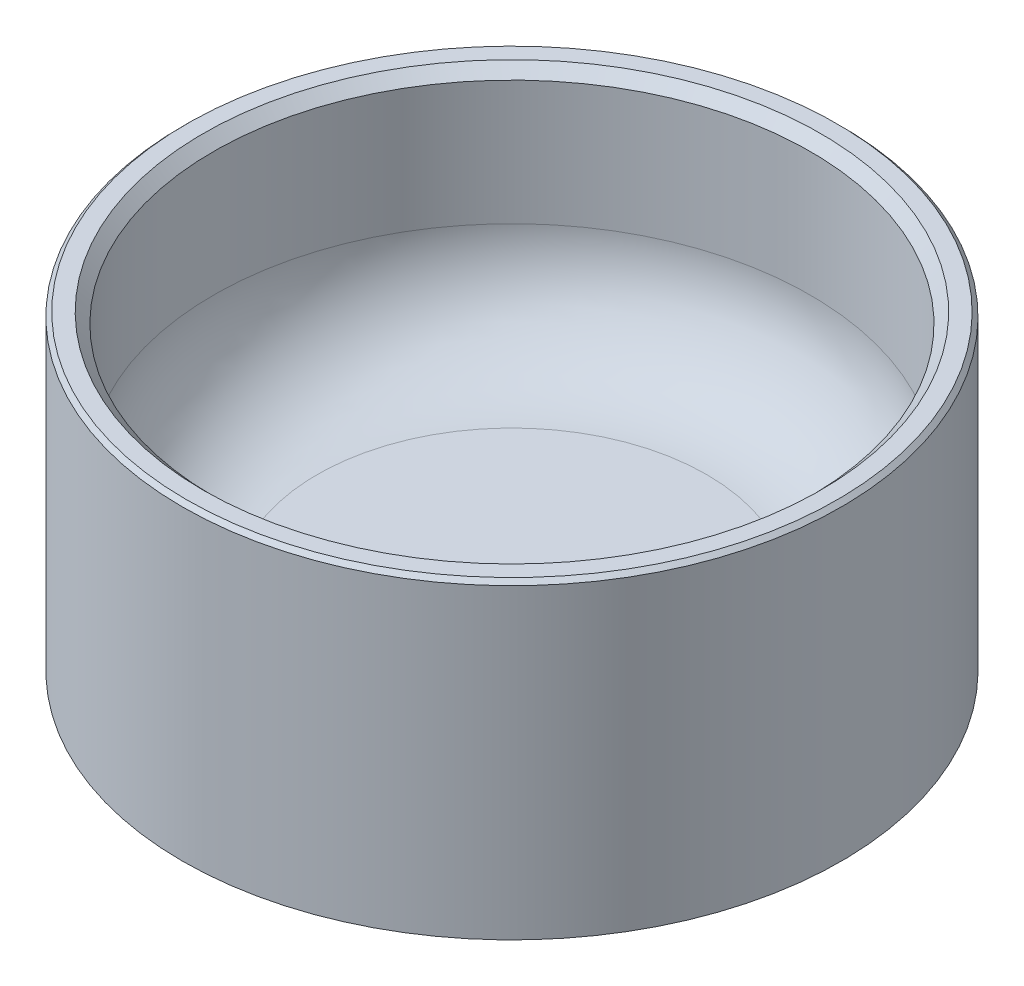
SolidWorks part; units mm, degrees
ref_plane "Front Plane" through (0, 0, 0) normal (0, 0, 1) x (1, 0, 0)
ref_plane "Top Plane" through (0, 0, 0) normal (0, 1, 0) x (1, 0, 0)
ref_plane "Right Plane" through (0, 0, 0) normal (1, 0, 0) x (0, 0, -1)
sketch "Sketch1" plane through (0, 0, 0) normal (0, 0, 1) x (1, 0, 0)
  line L0 (0, 0) -> (-12.4, 0)
  line L1 (-15.9, -2) -> (-15.9, 13)
  line L2 (-15.9, 13) -> (-14.4, 13)
  line L3 (-14.4, 13) -> (-14.4, 6.5)
  line L4 (-9.4, 1.5) -> (0, 1.5)
  line L5 (0, 1.5) -> (0, 0) construction
  line L6 (0, 0) -> (0, 1.5)
  line L7 (-14.4, -2) -> (-15.9, -2)
  arc A0 (-14.4, 6.5) -> (-9.4, 1.5) centre (-9.4, 6.5) ccw
  arc A1 (-14.4, -2) -> (-12.4, 0) centre (-12.4, -2) cw
  dimension "D5" = 5
  dimension "D6" = 2
  dimension "D1" = 15.9
  dimension "D2" = 15
  dimension "D3" = 1.5
  dimension "D4" = 1.5
  dimension "D7" = 1.5
  dimension "D8" = 12.4
revolve "Revolve1" add sketch "Sketch1" angle 360 about L5
chamfer "Chamfer1" distance 0.5 angle 45 1 edges at (0, 13, 14.4)
chamfer "Chamfer2" distance 0.2 angle 45 1 edges at (0, 13, 15.9)
